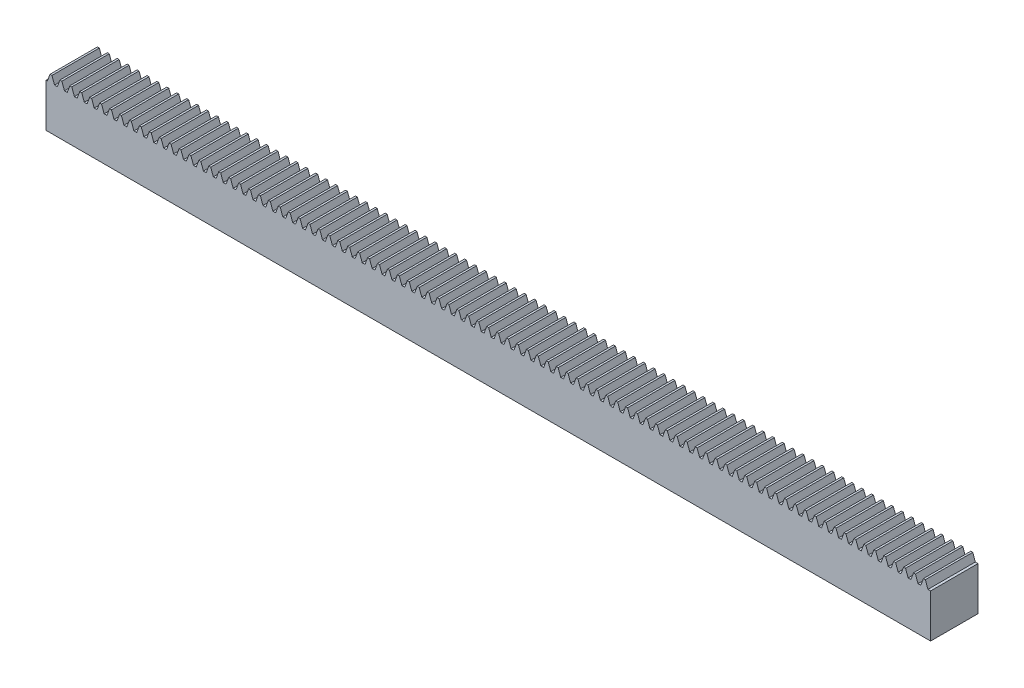
SolidWorks part; units mm, degrees
extrude "Blank" add sketch "BlankSke" against normal blind 15
sketch "BlankSke" plane through (0, 0, 0) normal (0, 0, 1) x (1, 0, 0)
  line L1 (0, 0) -> (280, 0)
  line L2 (0, 0) -> (0, 16)
  line L3 (0, 16) -> (280, 16)
  line L4 (280, 0) -> (280, 16)
  dimension "Length" = 280
  dimension "Blank_height" = 16
ref_plane "Plane1" through (0, 0, 0) normal (0, 0, 1) x (1, 0, 0)
ref_plane "Plane2" through (0, 0, 0) normal (0, 1, 0) x (1, 0, 0)
ref_plane "Plane3" through (0, 0, 0) normal (1, 0, 0) x (0, 0, -1)
sketch "HoldingSke" plane through (0, 0, 0) normal (0, 1, 0) x (1, 0, 0)
  line L0 (0, 0) -> (0.1392, 0.9903)
  line L1 (-15, 0) -> (100, 0) construction
  line L2 (0, 0) -> (-2.1039, 2.3779)
  line L3 (0, 0) -> (-11.863, 4.5341)
  line L4 (0, 0) -> (-0.1507, 8.6347)
  line L5 (0, 0) -> (-23.7986, -8.8762)
  line L6 (0, 0) -> (-10.5278, -7.1032)
  line L9 (-71.009, 38.7566) -> (192.105, 134.5223)
  line L10 (-76.2, 3.3779) -> (-61.2, 3.3779)
  line L11 (0, 0) -> (-15, 0)
  line L12 (-76.2, 101.6) -> (-76.162, 101.6)
  line L13 (24.9733, 27.94) -> (52.9518, 28.4284)
  line L14 (24.9733, 27.94) -> (24.9743, 27.94)
  line L15 (24.9733, 27.94) -> (100.4006, 29.5858)
  circle A0 centre (0, 0) radius 19.05
  circle A1 centre (0, 0) radius 7.5
  circle A2 centre (0, 0) radius 12.7
  dimension "MPH" = 15
  dimension "Diameter" = 38.1
  dimension "Num_teeth" = 91
  dimension "Pitch" = 1
  dimension "Show_teeth" = 998
  dimension "Thickness" = 12.7
  dimension "Ap" = 20
  dimension "Pitch_height" = 15
  dimension "Width" = 15
  dimension "Backlash" = 0.038
  dimension "Addendum_fac" = 1
  dimension "Dedendum_fac" = 1.25
  dimension "Clearance_fac" = 0.25
  dimension "Dedendum_add" = 0.001
  dimension "Length" = 280
  dimension "Module" = 1
sketch "TooCutSkeIll" plane through (0, 0, 0) normal (0, 0, 1) x (1, 0, 0)
  line L0 (-1.2538, 15.9737) -> (-0.5045, 13.9152)
  line L1 (-0.2687, 13.75) -> (0.2687, 13.75)
  line L2 (0.5045, 13.9152) -> (1.2538, 15.9737)
  line L3 (280, 16) -> (0, 16) construction
  line L4 (0, 0) -> (0, 64.897) construction
  line L5 (-13.208, 15) -> (12.954, 15) construction
  line L6 (0, 0) -> (280, 0) construction
  line L7 (0.8994, 15) -> (0.8994, 48.7463) construction
  line L8 (-0.8994, 15) -> (-0.8994, 48.7463) construction
  line L9 (1.2914, 16) -> (1.2914, 16.0254)
  line L10 (-1.2914, 16) -> (-1.2914, 16.0254)
  line L11 (-1.2914, 16.0254) -> (1.2914, 16.0254)
  arc A0 (0.2687, 13.75) -> (0.5045, 13.9152) centre (0.2687, 14.001) ccw
  arc A1 (-0.5045, 13.9152) -> (-0.2687, 13.75) centre (-0.2687, 14.001) ccw
  arc A2 (1.2914, 16) -> (1.2538, 15.9737) centre (1.2914, 15.96) ccw
  arc A3 (-1.2538, 15.9737) -> (-1.2914, 16) centre (-1.2914, 15.96) ccw
  dimension "Pitch_height" = 15
  dimension "Addendum_plus" = 1.0254
  dimension "Pressure_angle" = 20
  dimension "Gap_width" = 1.7988
  dimension "Dedendum" = 1.25
extrude "ToothCutIll" [suppressed] cut sketch "TooCutSkeIll" against normal through all
sketch "TooCutSkeSim" plane through (0, 0, 0) normal (0, 0, 1) x (1, 0, 0)
  line L0 (0.4444, 13.75) -> (-0.4444, 13.75)
  line L1 (1.2726, 16.0254) -> (0.4444, 13.75)
  line L2 (0, 17.4625) -> (0, 53.467) construction
  line L3 (1.2726, 16.0254) -> (-1.2726, 16.0254)
  line L6 (-1.2726, 16.0254) -> (-0.4444, 13.75)
  line L9 (-0.8994, 15) -> (0.8994, 15) construction
  line L10 (0, 0) -> (280, 0) construction
  line L11 (0.8994, 15) -> (0.8994, 53.467) construction
  line L12 (-0.8994, 15) -> (-0.8994, 53.467) construction
  dimension "Pitch_height" = 15
  dimension "Addendum_plus" = 1.0254
  dimension "Pressure_angle" = 20
  dimension "Gap_width" = 1.7988
  dimension "Dedendum" = 1.25
extrude "ToothCutSim" cut sketch "TooCutSkeSim" against normal through all
pattern_linear "TeethCuts" count 90 spacing 3.1416 along (1, 0, 0) of "ToothCutIll", "ToothCutSim"
sketch "Esquisse3" plane through (0, 0, 0) normal (0, -1, 0) x (1, 0, 0)
  line L0 (0, -7.5) -> (280, -7.5) construction
  line L1 (0, -15) -> (0, 0) construction
  line L2 (280, -15) -> (280, 0) construction
  circle A0 centre (19, -7.5) radius 1.25
  circle A1 centre (59, -7.5) radius 1.25
  circle A2 centre (99, -7.5) radius 1.25
  circle A3 centre (139, -7.5) radius 1.25
  circle A4 centre (179, -7.5) radius 1.25
  circle A5 centre (219, -7.5) radius 1.25
  circle A6 centre (259, -7.5) radius 1.25
  point P9 (59.4419, -7.5)
  dimension "D1" = 2.5
  dimension "D2" = 19
  dimension "D4" = 40
  dimension "D3" = 7
extrude "Enlèv. mat.-Extru.3" cut sketch "Esquisse3" against normal blind 10
sketch "Esquisse1" plane through (0, 0, 0) normal (0, 0, 1) x (1, 0, 0)
  line L0 (140, 0) -> (140, 7.9223) construction
  line L1 (0, 0) -> (280, 0) construction
  line L2 (141.3717, 16) -> (141.3717, 13.75) construction
  line L3 (140.1083, 16) -> (139.4934, 16) construction
  line L4 (141.2717, 16) -> (141.2717, 5)
  line L5 (141.2717, 5) -> (136.2717, 5)
  line L6 (136.2717, 5) -> (136.2717, 0)
  line L7 (136.2717, 0) -> (280, 0)
  line L8 (280, 0) -> (280, 16)
  line L9 (280, 16) -> (141.2717, 16)
  line L10 (140.9272, 13.75) -> (141.8161, 13.75) construction
  dimension "D1" = 5
  dimension "D2" = 5
  dimension "D3" = 0.1
extrude "Enlèv. mat.-Extru.1" [suppressed] cut sketch "Esquisse1" against normal through all
sketch "Esquisse2" [suppressed] plane through (0, 0, 0) normal (0, 0, 1) x (1, 0, 0)
  line L0 (140, 0) -> (140, 9.6353) construction
  line L1 (0, 0) -> (280, 0) construction
  line L2 (141.3717, 13.75) -> (141.3717, 11.7709) construction
  line L3 (140.9272, 13.75) -> (141.8161, 13.75) construction
  line L4 (136.2717, 0) -> (136.2717, 5.1)
  line L5 (136.2717, 5.1) -> (141.3717, 5.1)
  line L6 (141.3717, 5.1) -> (141.3717, 19)
  line L7 (141.3717, 19) -> (0, 19)
  line L8 (0, 19) -> (0, 0)
  line L9 (0, 0) -> (136.2717, 0)
  line L10 (140.1179, 19) -> (141.3717, 19) construction
  dimension "D1" = 5.1
  dimension "D2" = 5.1
  dimension "D3" = 19
extrude "Enlèv. mat.-Extru.2" [suppressed] cut sketch "Esquisse2" against normal through all
equation "' \"Module@HoldingSke\" = 6.35"
equation "' \"Num_teeth@HoldingSke\" = 12"
equation "' \"Ap@HoldingSke\" =  20"
equation "' \"Ap@HoldingSke\" = 20"
equation "' \"Width@HoldingSke\" = 0.25 * 25.4"
equation "' \"Show_teeth@HoldingSke\" = 500"
equation "' \"Backlash@HoldingSke\" = 0.009 * 25.4"
equation "' \"Addendum_fac@HoldingSke\" = 1.0"
equation "' \"Dedendum_fac@HoldingSke\" = 1.25"
equation "' \"Dedendum_add@HoldingSke\" = 0.00005 * 25.4"
equation "' \"Clearance_fac@HoldingSke\" = 0.25"
equation "' \"Pitch_height@HoldingSke\" = 1 * 25.4"
equation "' \"Length@HoldingSke\" = 4.71 * 25.4"
equation "\"Pitch@HoldingSke\" = 1 / \"Module@HoldingSke\""
equation "\"MPH@HoldingSke\" = \"Dedendum_fac@HoldingSke\" / \"Pitch@HoldingSke\" + 2 * \"Dedendum_add@HoldingSke\" + 0.002 * 25.4"
equation "\"MPH@HoldingSke\" = ((sgn( \"MPH@HoldingSke\" - \"Pitch_height@HoldingSke\")+1)*( \"MPH@HoldingSke\" - \"Pitch_height@HoldingSke\"))/2 + \"Pitch_height@HoldingSke\""
equation "\"Blank_height@BlankSke\" = \"Pitch_height@HoldingSke\" + \"Addendum_fac@HoldingSke\"  / \"Pitch@HoldingSke\" "
equation "\"Length@BlankSke\" =  \"Length@HoldingSke\""
equation "\"Face_width@Blank\" = \"Width@HoldingSke\""
equation "\"Pressure_angle@TooCutSkeIll\" = \"Ap@HoldingSke\""
equation "\"Addendum_plus@TooCutSkeIll\" =  \"Addendum_fac@HoldingSke\"  / \"Pitch@HoldingSke\" + 0.001 *25.4"
equation "\"Dedendum@TooCutSkeIll\" = \"Dedendum_fac@HoldingSke\"  / \"Pitch@HoldingSke\""
equation "\"Pitch_height@TooCutSkeIll\" =  \"MPH@HoldingSke\""
equation "\"Gap_width@TooCutSkeIll\" = 3.14159265 / 2 / \"Pitch@HoldingSke\" + 6 * \"Backlash@HoldingSke\""
equation "\"Pressure_angle@TooCutSkeSim\" = \"Ap@HoldingSke\""
equation "\"Addendum_plus@TooCutSkeSim\" =  \"Addendum_fac@HoldingSke\"  / \"Pitch@HoldingSke\" + 0.001 * 25.4"
equation "\"Dedendum@TooCutSkeSim\" = \"Dedendum_fac@HoldingSke\"  / \"Pitch@HoldingSke\""
equation "\"Pitch_height@TooCutSkeSim\" =  \"MPH@HoldingSke\""
equation "\"Gap_width@TooCutSkeSim\" = 3.14159265 / 2 / \"Pitch@HoldingSke\" + 6 * \"Backlash@HoldingSke\""
equation "\"Root_fillet@TooCutSkeIll\" = \"Clearance_fac@HoldingSke\" / \"Pitch@HoldingSke\" + \"Dedendum_add@HoldingSke\""
equation "\"Break_rad@TooCutSkeIll\" = 0.02 / \"Pitch@HoldingSke\" * 2"
equation "\"Linear_pitch@TeethCuts\" = 3.14159265 / \"Pitch@HoldingSke\""
equation "\"Num_teeth@HoldingSke\" = int( ( \"Length@HoldingSke\" + 0 ) / (3.14159265 / \"Pitch@HoldingSke\")) + 0.9999  + 1"
equation " \"Num_teeth@TeethCuts\" = int( \"Show_teeth@HoldingSke\" ) + 1"
equation " \"Num_teeth@TeethCuts\" = ((sgn( \"Num_teeth@TeethCuts\" - \"Num_teeth@HoldingSke\" )-1)*( \"Num_teeth@TeethCuts\" - \"Num_teeth@HoldingSke\" ))/-2+ \"Num_teeth@HoldingSke\""
equation " \"Num_teeth@TeethCuts\" = ((sgn( \"Num_teeth@TeethCuts\" - 2.0)+1)*( \"Num_teeth@TeethCuts\" - 2.0))/2 +2.0"
